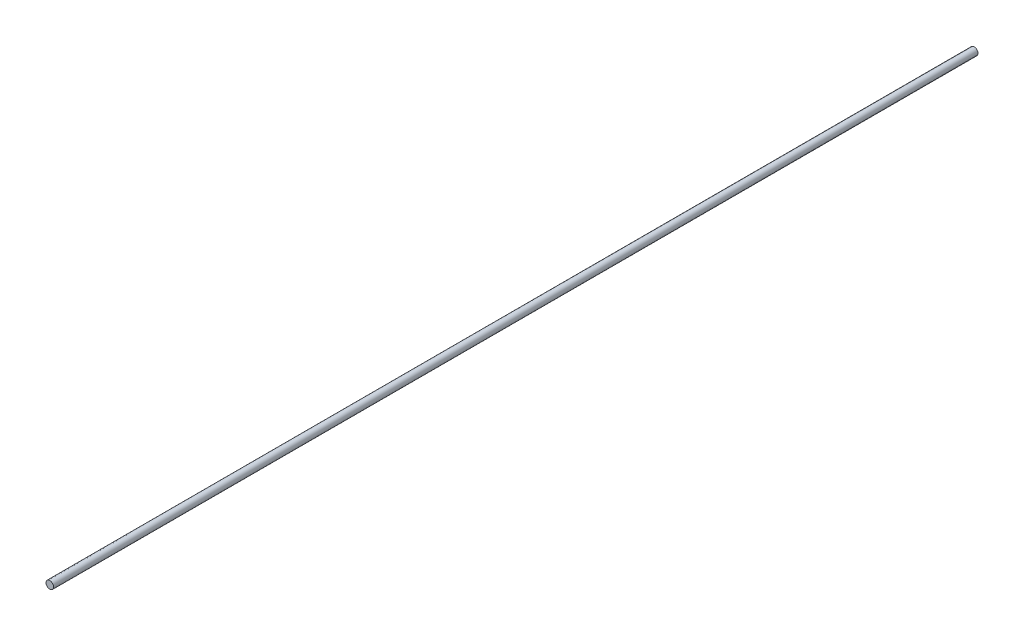
SolidWorks part; units mm, degrees
ref_plane "Front Plane" through (0, 0, 0) normal (0, 0, 1) x (1, 0, 0)
ref_plane "Top Plane" through (0, 0, 0) normal (0, 1, 0) x (1, 0, 0)
ref_plane "Right Plane" through (0, 0, 0) normal (1, 0, 0) x (0, 0, -1)
sketch "Sketch1" plane through (0, 0, 0) normal (0, 0, 1) x (1, 0, 0)
  circle A0 centre (0, 0) radius 2.5
extrude "Boss-Extrude1" add sketch "Sketch1" against normal blind 609.6
